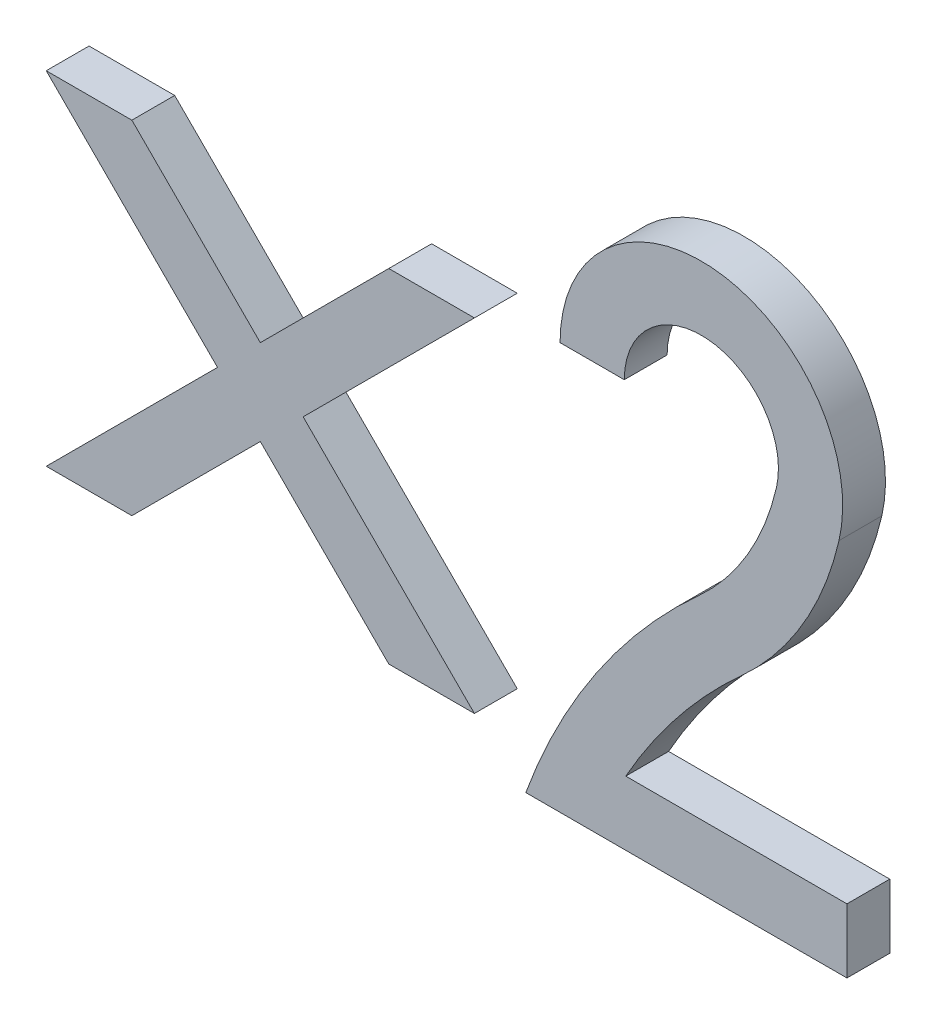
SolidWorks part; units mm, degrees
ref_plane "Front Plane" through (0, 0, 0) normal (0, 0, 1) x (1, 0, 0)
ref_plane "Top Plane" through (0, 0, 0) normal (0, 1, 0) x (1, 0, 0)
ref_plane "Right Plane" through (0, 0, 0) normal (1, 0, 0) x (0, 0, -1)
sketch "Sketch1" plane through (0, 0, 0) normal (0, 0, 1) x (1, 0, 0)
  line L0 (-50, 40) -> (-10, 0)
  line L1 (30, -40) -> (50, -40)
  line L2 (50, -40) -> (10, 0)
  line L3 (-30, 40) -> (-50, 40)
  line L4 (30, 40) -> (50, 40)
  line L5 (50, 40) -> (10, 0)
  line L6 (-30, -40) -> (-50, -40)
  line L7 (-50, -40) -> (-10, 0)
  line L8 (85.3427, -35) -> (137, -35)
  line L9 (62, -50) -> (137, -50)
  line L10 (0, -55) -> (0, 55) construction
  line L11 (55, 0) -> (-55, 0) construction
  line L12 (70, 45) -> (85, 45)
  line L13 (137, -50) -> (137, -35)
  line L14 (0, 10) -> (30, 40)
  line L15 (0, -10) -> (-30, -40)
  line L16 (0, 10) -> (-30, 40)
  line L17 (0, -10) -> (30, -40)
  arc A0 (85, 45) -> (120.5343, 40.9322) centre (103, 45) cw
  arc A1 (120.5343, 40.9322) -> (102.3421, 10) centre (62.0865, 54.4915) cw
  arc A2 (102.3421, 10) -> (62, -50) centre (202.9809, -101.2287) ccw
  arc A3 (70, 45) -> (135.1463, 37.5424) centre (103, 45) cw
  arc A4 (135.1463, 37.5424) -> (112.406, -1.1229) centre (62.0865, 54.4915) cw
  arc A5 (112.406, -1.1229) -> (85.3427, -35) centre (202.9809, -101.2287) ccw
  point P6 (0, 10)
  point P16 (-10, 0)
  point P18 (10, 0)
  point P19 (0, -10)
  point P20 (62, -50)
  point P25 (102.3292, 10)
  dimension "D9" = 18
  dimension "D10" = 60
  dimension "D11" = 150
  dimension "D2" = 20
  dimension "D3" = 100
  dimension "D4" = 80
  dimension "D5" = 10
  dimension "D6" = 12
  dimension "D7" = 5
  dimension "D8" = 20
  dimension "D12" = 75
  dimension "D1" = 15
extrude "Boss-Extrude1" add sketch "Sketch1" along normal blind 10
